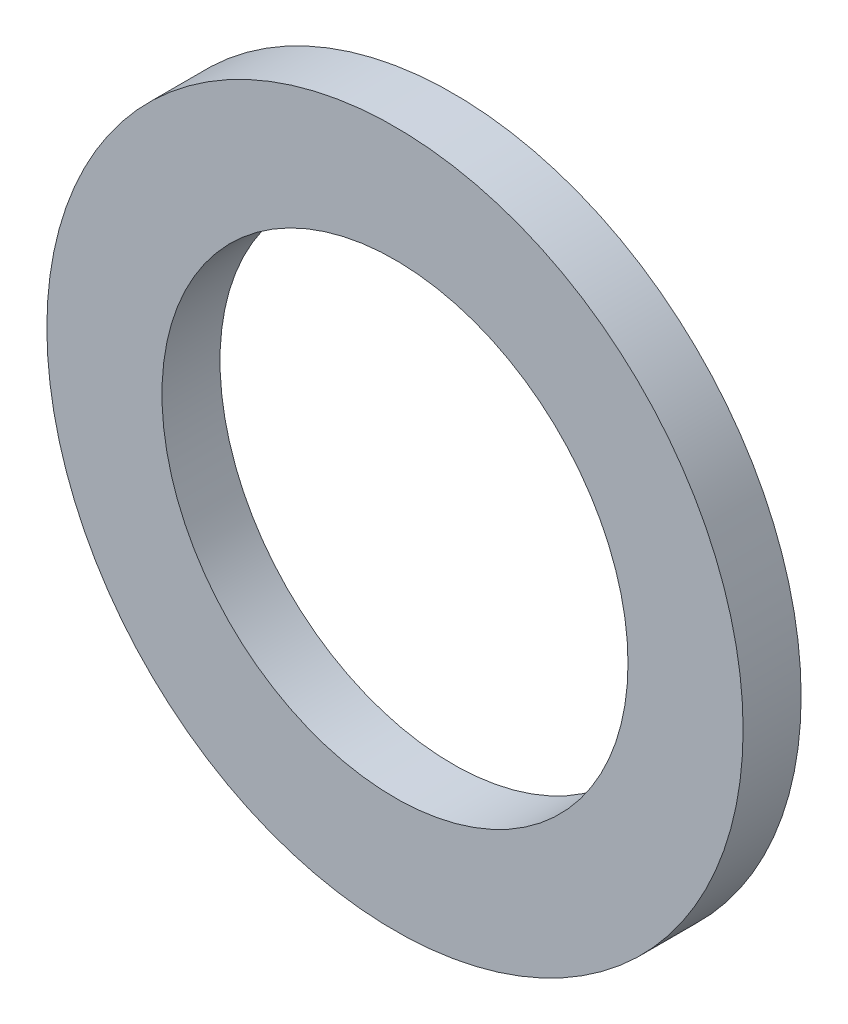
SolidWorks part; units mm, degrees
material "Commercial Bronze, UNS C22000 (90-10 Bronze)"
ref_plane "Front Plane" through (0, 0, 0) normal (0, 0, 1) x (1, 0, 0)
ref_plane "Top Plane" through (0, 0, 0) normal (0, 1, 0) x (1, 0, 0)
ref_plane "Right Plane" through (0, 0, 0) normal (1, 0, 0) x (0, 0, -1)
sketch "Sketch1" plane through (0, 0, 0) normal (0, 0, 1) x (1, 0, 0)
  circle A0 centre (0, 0) radius 9.525
  circle A1 centre (0, 0) radius 6.3754
  dimension "D1" = 19.05
  dimension "ID" = 12.7508
extrude "Extrude1" add sketch "Sketch1" along normal mid plane 1.5875
sketch "Sketch2" plane through (0, 0, 0) normal (1, 0, 0) x (0, 0, -1)
  line L0 (-0.7937, -6.3754) -> (0.7937, -6.3754) construction
  line L3 (0.7937, 6.3754) -> (-0.7937, 6.3754) construction
  line L5 (-0.7937, -6.3754) -> (0.7937, -6.3754)
  line L6 (0.7937, 6.3754) -> (-0.7937, 6.3754)
sketch "Sketch4" plane through (0, 0, 0.7937) normal (0, 0, 1) x (1, 0, 0)
  line L0 (0, 0) -> (-4.5081, 4.5081)
  line L1 (0, -0.8731) -> (0, 0.8731) construction
  circle A0 centre (0, 0) radius 6.3754 construction
  dimension "D1" = 45
